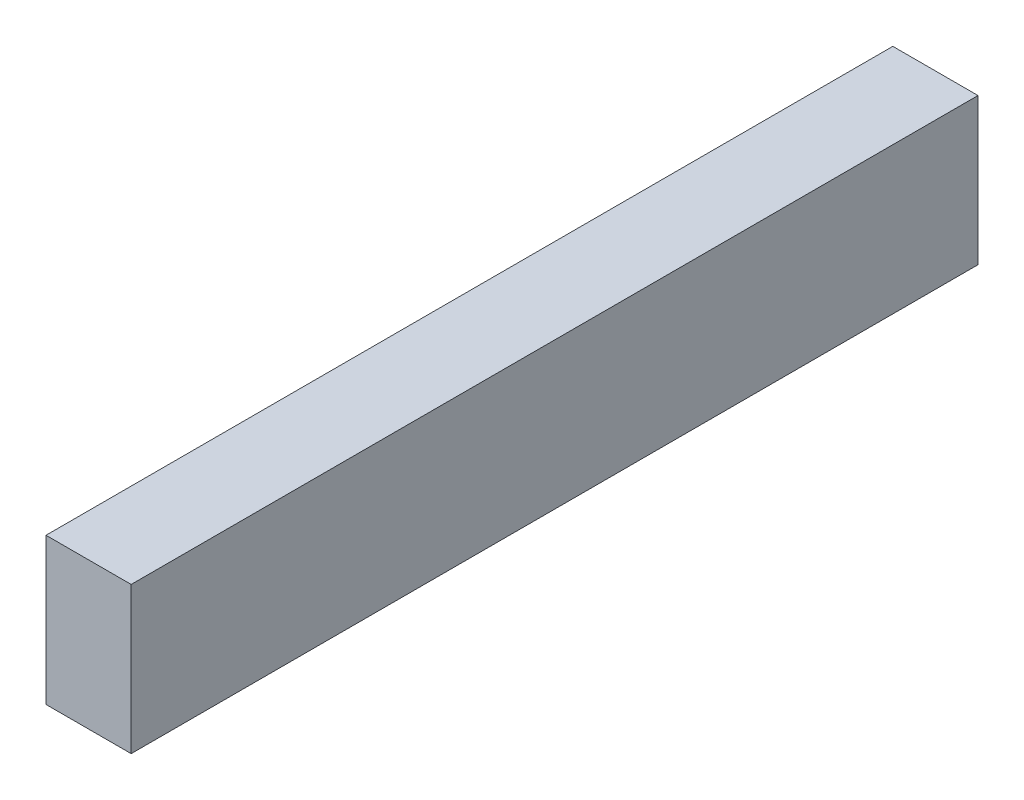
SolidWorks part; units mm, degrees
material "Natural Rubber"
ref_plane "Front Plane" through (0, 0, 0) normal (0, 0, 1) x (1, 0, 0)
ref_plane "Top Plane" through (0, 0, 0) normal (0, 1, 0) x (1, 0, 0)
ref_plane "Right Plane" through (0, 0, 0) normal (1, 0, 0) x (0, 0, -1)
sketch "Sketch1" plane through (0, 0, 0) normal (0, 1, 0) x (1, 0, 0)
  line L0 (0, -13.208) -> (-1.3284, -13.208)
  line L1 (0, -13.208) -> (0, 0)
  line L2 (-1.3284, -13.208) -> (-1.3284, 0)
  line L3 (-1.3284, 0) -> (0, 0)
  dimension "D1" = 13.208
  dimension "D2" = 1.3284
extrude "Boss-Extrude1" add sketch "Sketch1" along normal blind 2.286
